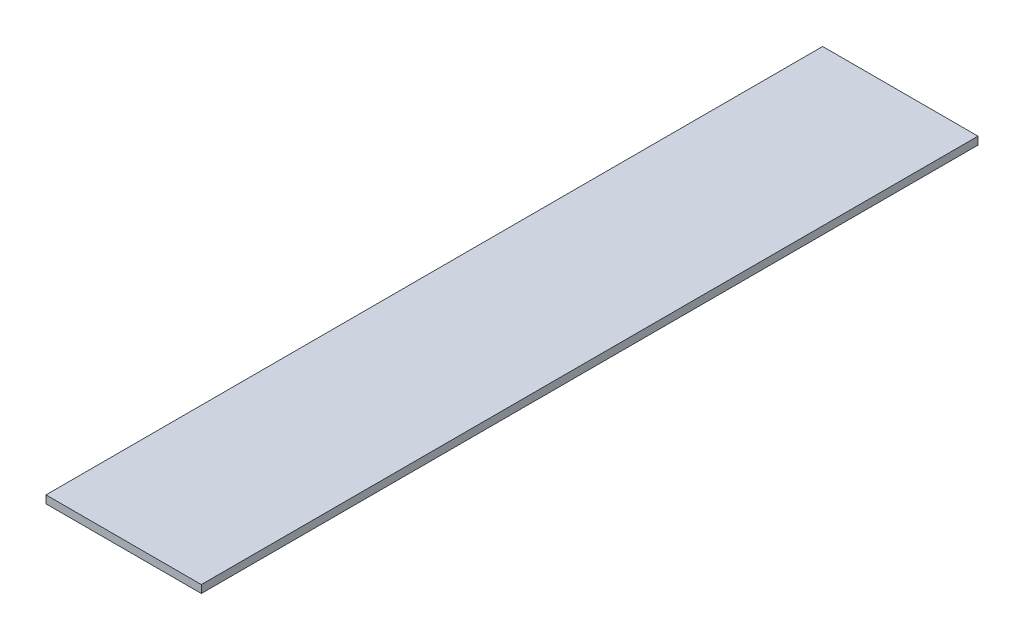
SolidWorks part; units mm, degrees
ref_plane "Plan de face" through (0, 0, 0) normal (0, 0, 1) x (1, 0, 0)
ref_plane "Plan de dessus" through (0, 0, 0) normal (0, 1, 0) x (1, 0, 0)
ref_plane "Plan de droite" through (0, 0, 0) normal (1, 0, 0) x (0, 0, -1)
sketch "Esquisse1" plane through (0, 0, 0) normal (0, 1, 0) x (1, 0, 0)
  line L0 (0, 0) -> (0, 200)
  line L1 (0, 200) -> (40, 200)
  line L2 (40, 200) -> (40, 0)
  line L3 (40, 0) -> (0, 0)
  dimension "D1" = 200
  dimension "D2" = 40
extrude "Boss.-Extru.1" add sketch "Esquisse1" along normal blind 2
